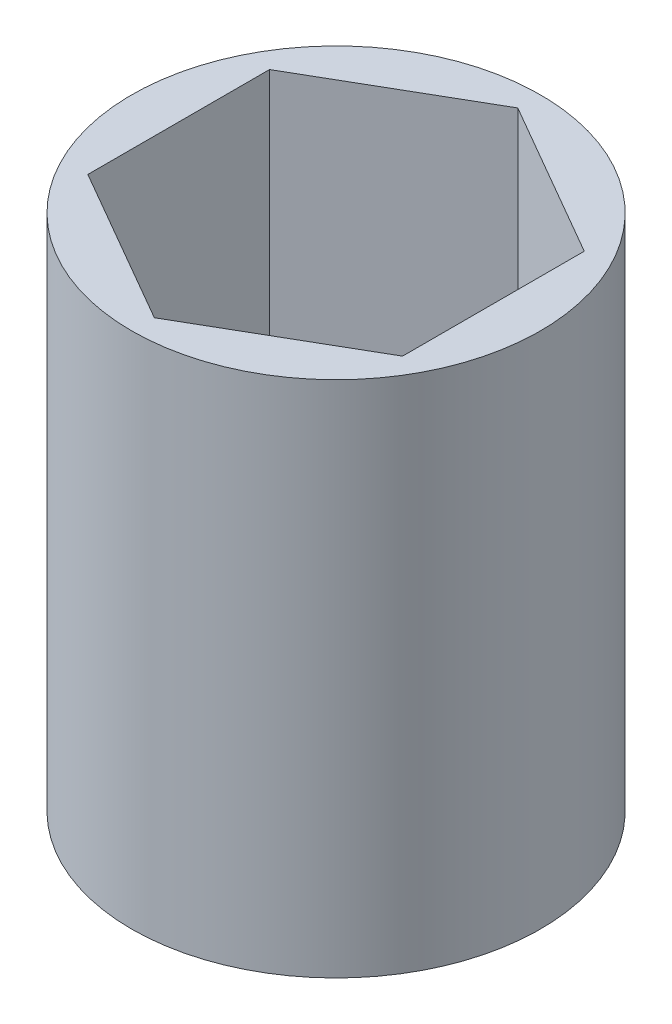
SolidWorks part; units mm, degrees
ref_plane "Front Plane" through (0, 0, 0) normal (0, 0, 1) x (1, 0, 0)
ref_plane "Top Plane" through (0, 0, 0) normal (0, 1, 0) x (1, 0, 0)
ref_plane "Right Plane" through (0, 0, 0) normal (1, 0, 0) x (0, 0, -1)
sketch "Sketch1" plane through (0, 0, 0) normal (0, 1, 0) x (1, 0, 0)
  line L1 (0, 7.7942) -> (-6.75, 3.8971)
  line L2 (-6.75, 3.8971) -> (-6.75, -3.8971)
  line L3 (-6.75, -3.8971) -> (0, -7.7942)
  line L4 (0, -7.7942) -> (6.75, -3.8971)
  line L5 (6.75, -3.8971) -> (6.75, 3.8971)
  line L6 (6.75, 3.8971) -> (0, 7.7942)
  circle A0 centre (0, 0) radius 8.7688
  circle A1 centre (0, 0) radius 6.75 construction
  dimension "D1" = 13.5
extrude "Boss-Extrude1" add sketch "Sketch1" along normal blind 22.225
